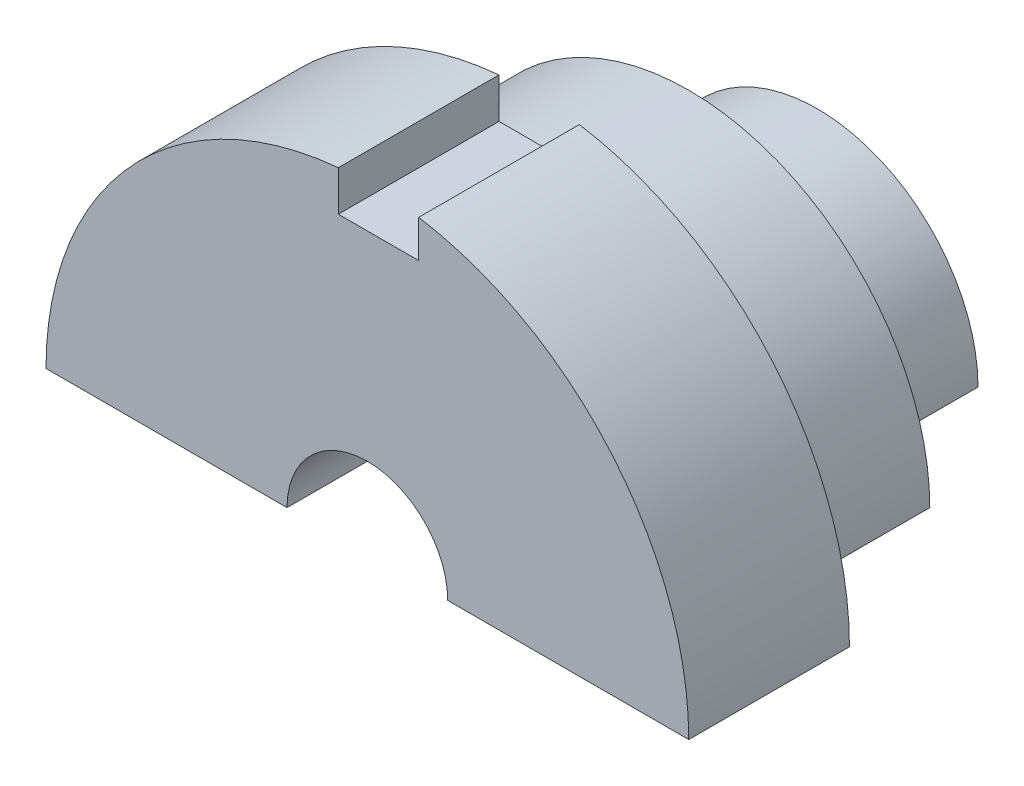
SolidWorks part; units mm, degrees
ref_plane "Front Plane" through (0, 0, 0) normal (0, 0, 1) x (1, 0, 0)
ref_plane "Top Plane" through (0, 0, 0) normal (0, 1, 0) x (1, 0, 0)
ref_plane "Right Plane" through (0, 0, 0) normal (1, 0, 0) x (0, 0, -1)
sketch "Sketch2" plane through (0, 0, 0) normal (0, 0, 1) x (1, 0, 0)
  line L0 (0, 0) -> (40, 0)
  arc A0 (0, 0) -> (40, 0) centre (20, 0) cw
  dimension "D1" = 20
  dimension "D2" = 40
extrude "Boss-Extrude1" add sketch "Sketch2" along normal blind 10
sketch "Sketch3" plane through (0, 0, 10) normal (0, 0, 1) x (1, 0, 0)
  line L1 (23.1928, 21.9456) -> (18.1928, 21.9456)
  line L2 (23.1928, 21.9456) -> (23.1928, 17.4124)
  line L3 (23.1928, 17.4124) -> (18.1928, 17.4124)
  line L4 (18.1928, 21.9456) -> (18.1928, 17.4124)
  line L5 (23.1928, 21.9456) -> (18.1928, 17.4124) construction
  line L6 (23.1928, 17.4124) -> (18.1928, 21.9456) construction
  point P4 (20.6928, 19.679)
  dimension "D1" = 5
extrude "Cut-Extrude1" cut sketch "Sketch3" against normal blind 19 and the other way blind 12
sketch "Sketch4" plane through (0, 0, 0) normal (0, 0, -1) x (-1, 0, 0)
  line L0 (0, 0) -> (-40, 0) construction
  line L1 (-35, 0) -> (-5, 0)
  arc A0 (-35, 0) -> (-5, 0) centre (-20, 0) cw
  dimension "D1" = 15
extrude "Boss-Extrude2" add sketch "Sketch4" along normal blind 10
sketch "Sketch5" plane through (0, 0, -10) normal (0, 0, -1) x (-1, 0, 0)
  line L0 (-35, 0) -> (-5, 0) construction
  line L1 (-30, 0) -> (-10, 0)
  arc A0 (-30, 0) -> (-10, 0) centre (-20, 0) cw
  dimension "D1" = 10
extrude "Boss-Extrude3" add sketch "Sketch5" along normal blind 8
sketch "Sketch6" plane through (0, 0, -18) normal (0, 0, -1) x (-1, 0, 0)
  line L0 (-30, 0) -> (-10, 0) construction
  line L1 (-25, 0) -> (-15, 0)
  arc A0 (-25, 0) -> (-15, 0) centre (-20, 0) cw
  dimension "D1" = 5
extrude "Cut-Extrude3" cut sketch "Sketch6" against normal blind 41
